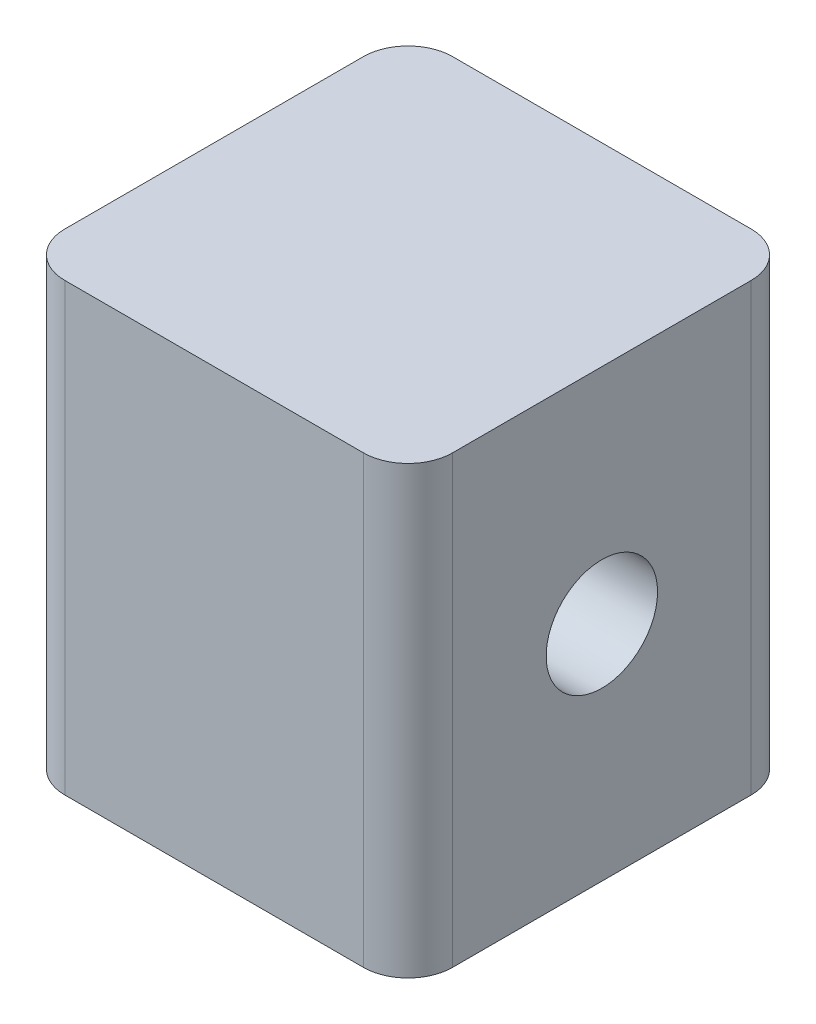
SolidWorks part; units mm, degrees
material "AISI 304"
ref_plane "Front" through (0, 0, 0) normal (0, 0, 1) x (1, 0, 0)
ref_plane "Top" through (0, 0, 0) normal (0, 1, 0) x (1, 0, 0)
ref_plane "Right" through (0, 0, 0) normal (1, 0, 0) x (0, 0, -1)
sketch "Sketch4" plane through (0, 0, 0) normal (0, 1, 0) x (1, 0, 0)
  line L1 (-11.049, -11.049) -> (11.049, -11.049)
  line L2 (-11.049, -11.049) -> (-11.049, 11.049)
  line L3 (-11.049, 11.049) -> (11.049, 11.049)
  line L4 (11.049, -11.049) -> (11.049, 11.049)
  line L5 (-11.049, -11.049) -> (11.049, 11.049) construction
  line L6 (-11.049, 11.049) -> (11.049, -11.049) construction
  point P0 (0, 0)
  dimension "D1" = 22.098
  dimension "D2" = 22.098
extrude "Boss-Extrude2" add sketch "Sketch4" along normal mid plane 25.4
fillet "Fillet1" radius 2.54 4 edges at (-11.049, 0, 11.049) (11.049, 0, 11.049) (11.049, 0, -11.049) (-11.049, 0, -11.049)
sketch "Sketch6" plane through (11.049, 0, 0) normal (1, 0, 0) x (0, 0, -1)
  circle A0 centre (0, 0) radius 3.175
  dimension "D1" = 6.35
extrude "Cut-Extrude1" cut sketch "Sketch6" against normal through all
